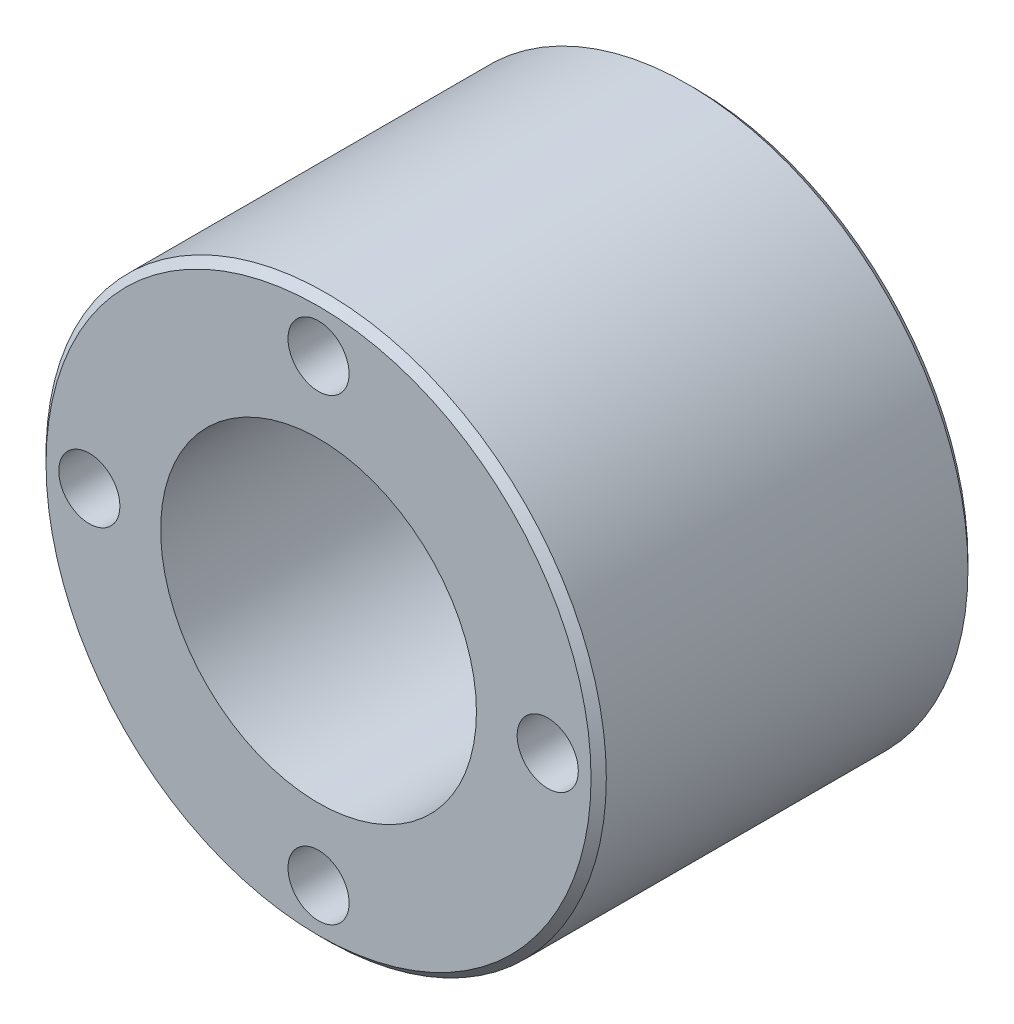
SolidWorks part; units mm, degrees
material "Chrome Stainless Steel"
ref_plane "Front Plane" through (0, 0, 0) normal (0, 0, 1) x (1, 0, 0)
ref_plane "Top Plane" through (0, 0, 0) normal (0, 1, 0) x (1, 0, 0)
ref_plane "Right Plane" through (0, 0, 0) normal (1, 0, 0) x (0, 0, -1)
sketch "Sketch1" plane through (0, 0, 0) normal (0, 0, 1) x (1, 0, 0)
  circle A0 centre (0, 0) radius 11
  circle A1 centre (0, 0) radius 6.2
  dimension "D1" = 22
  dimension "D2" = 4.8
extrude "Boss-Extrude1" add sketch "Sketch1" along normal blind 14.8
sketch "Sketch2" plane through (0, 0, 14.8) normal (0, 0, 1) x (1, 0, 0)
  circle A0 centre (0, 0) radius 9 construction
  circle A1 centre (0, 0) radius 11 construction
  circle A2 centre (0, 9) radius 1.2
  circle A3 centre (9, 0) radius 1.2
  circle A4 centre (0, -9) radius 1.2
  circle A5 centre (-9, 0) radius 1.2
  point P16 (0, 0)
  dimension "D1" = 2
  dimension "D2" = 2.4
  dimension "D3" = 4
extrude "Cut-Extrude1" cut sketch "Sketch2" against normal blind 14.8
chamfer "Chamfer1" distance 0.3 angle 45 2 edges at (11, 0, 0) (11, 0, 14.8)
